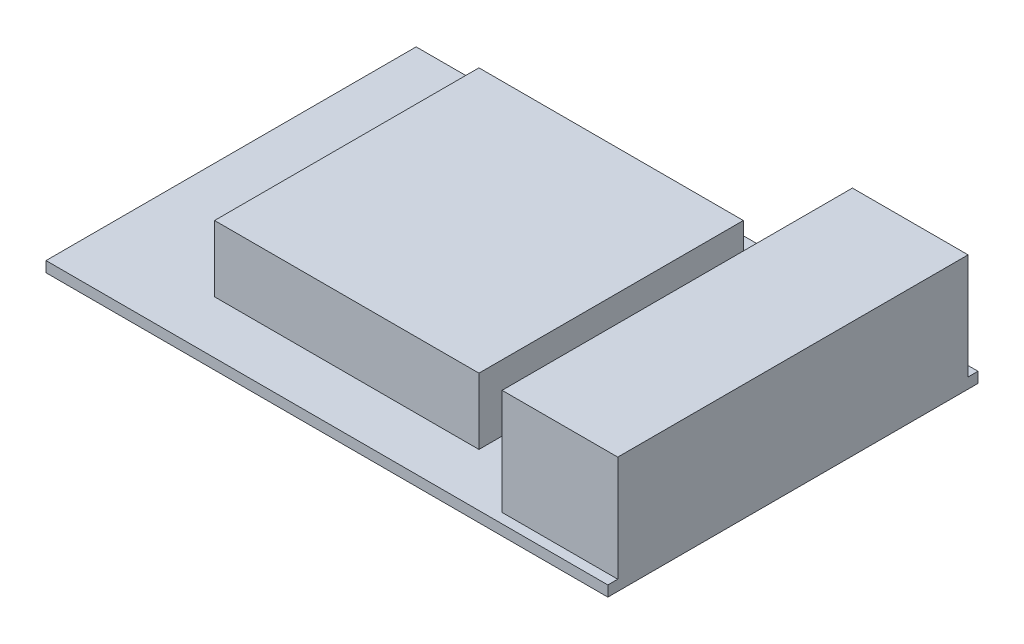
SolidWorks part; units mm, degrees
ref_plane "Front Plane" through (0, 0, 0) normal (0, 0, 1) x (1, 0, 0)
ref_plane "Top Plane" through (0, 0, 0) normal (0, 1, 0) x (1, 0, 0)
ref_plane "Right Plane" through (0, 0, 0) normal (1, 0, 0) x (0, 0, -1)
sketch "SK_Board" plane through (0, 0, 0) normal (0, 0, 1) x (1, 0, 0)
  line L0 (-42.5, 0) -> (42.5, 0)
  line L1 (42.5, 0) -> (42.5, 1.6)
  line L2 (42.5, 1.6) -> (-42.5, 1.6)
  line L3 (-42.5, 1.6) -> (-42.5, 0)
extrude "Board" add sketch "SK_Board" along normal mid plane 56
sketch "SK_Cooler" plane through (0, 0, 0) normal (0, 0, 1) x (1, 0, 0)
  line L0 (-25, 1.6) -> (15, 1.6)
  line L1 (15, 1.6) -> (15, 11.6)
  line L2 (15, 11.6) -> (-25, 11.6)
  line L3 (-25, 11.6) -> (-25, 1.6)
extrude "Cooler" add sketch "SK_Cooler" along normal mid plane 40
sketch "SK_Ports" plane through (0, 0, 0) normal (0, 0, 1) x (1, 0, 0)
  line L0 (25, 1.6) -> (42.5, 1.6)
  line L1 (42.5, 1.6) -> (42.5, 17.6)
  line L2 (42.5, 17.6) -> (25, 17.6)
  line L3 (25, 17.6) -> (25, 1.6)
extrude "Ports" add sketch "SK_Ports" along normal mid plane 53
